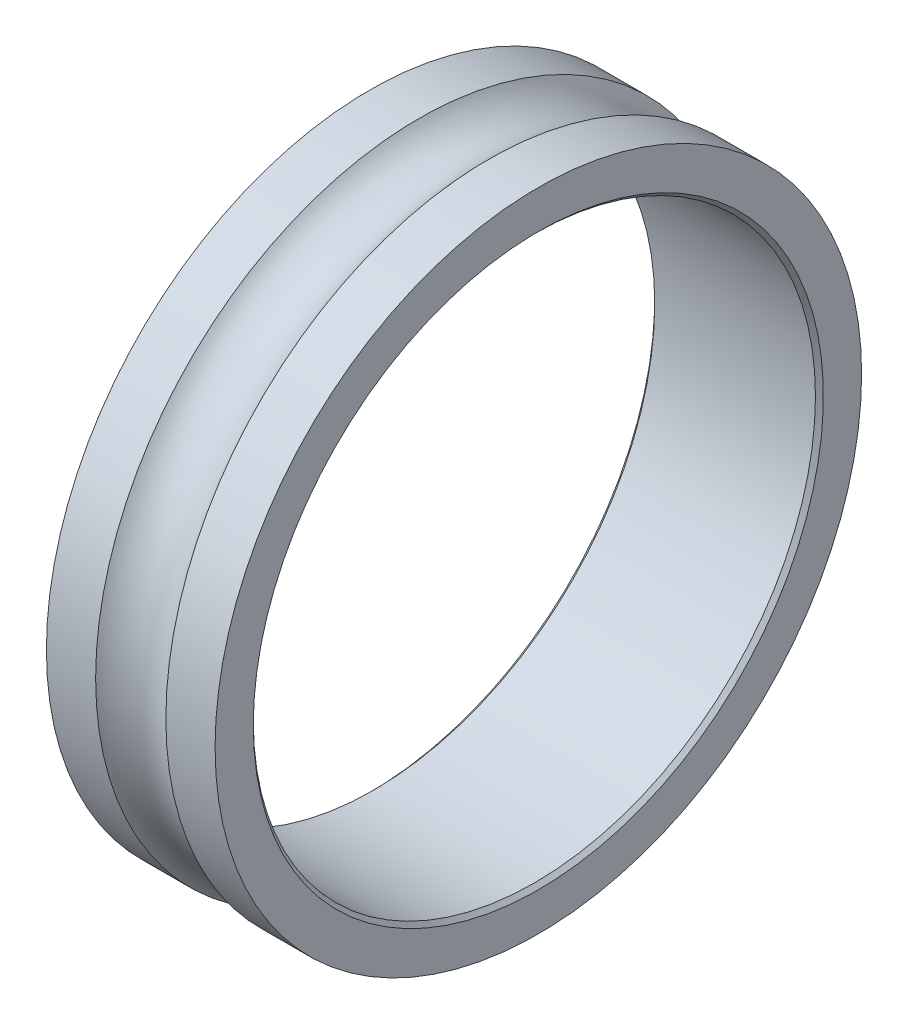
SolidWorks part; units mm, degrees
material "1.2083 (X40Cr14)"
ref_plane "Płaszczyzna przednia" through (0, 0, 0) normal (0, 0, 1) x (1, 0, 0)
ref_plane "Płaszczyzna górna" through (0, 0, 0) normal (0, 1, 0) x (1, 0, 0)
ref_plane "Płaszczyzna prawa" through (0, 0, 0) normal (1, 0, 0) x (0, 0, -1)
sketch "Szkic1" plane through (0, 0, 0) normal (0, 0, 1) x (1, 0, 0)
  line L0 (0, -7.5) -> (0, 7.5) construction
  line L1 (-1.5, 0) -> (1.5, 0) construction
  line L2 (-1.4293, 5) -> (1.4293, 5)
  line L3 (1.4293, 5) -> (1.5, 5.0707)
  line L4 (1.5, 5.0707) -> (1.5, 5.75)
  line L5 (1.5, 5.75) -> (0.6245, 5.75)
  line L6 (-1.5, 6.75) -> (-0.6245, 6.75)
  line L7 (1.5, 6.75) -> (1.5, 7.4293)
  line L8 (1.5, 7.4293) -> (1.4293, 7.5)
  line L9 (1.4293, 7.5) -> (-1.4293, 7.5)
  line L10 (-1.4293, 5) -> (-1.5, 5.0707)
  line L11 (-1.5, 5.0707) -> (-1.5, 5.75)
  line L12 (-1.5, 7.4293) -> (-1.4293, 7.5)
  line L13 (-1.5, 6.75) -> (-1.5, 7.4293)
  line L14 (0.6245, 6.75) -> (1.5, 6.75)
  line L15 (-0.6245, 5.75) -> (-1.5, 5.75)
  arc A0 (0.6245, 6.75) -> (-0.6245, 6.75) centre (0, 6.25) ccw
  arc A1 (-0.6245, 5.75) -> (0.6245, 5.75) centre (0, 6.25) ccw
  point P6 (0, 0)
  point P21 (0, 5)
  point P26 (0, 7.5)
  point P31 (0, 5.45)
  dimension "D8" = 1.6
  dimension "D1" = 10
  dimension "D2" = 0.1
  dimension "D3" = 15
  dimension "D4" = 1
  dimension "D5" = 135
  dimension "D6" = 3
  dimension "D7" = 0.5
revolve "Obrót1" add sketch "Szkic1" angle 360 about L1
sketch "Szkic4" plane through (0, 0, 0) normal (1, 0, 0) x (0, 0, -1)
  circle A0 centre (0, 0) radius 5.45 construction
